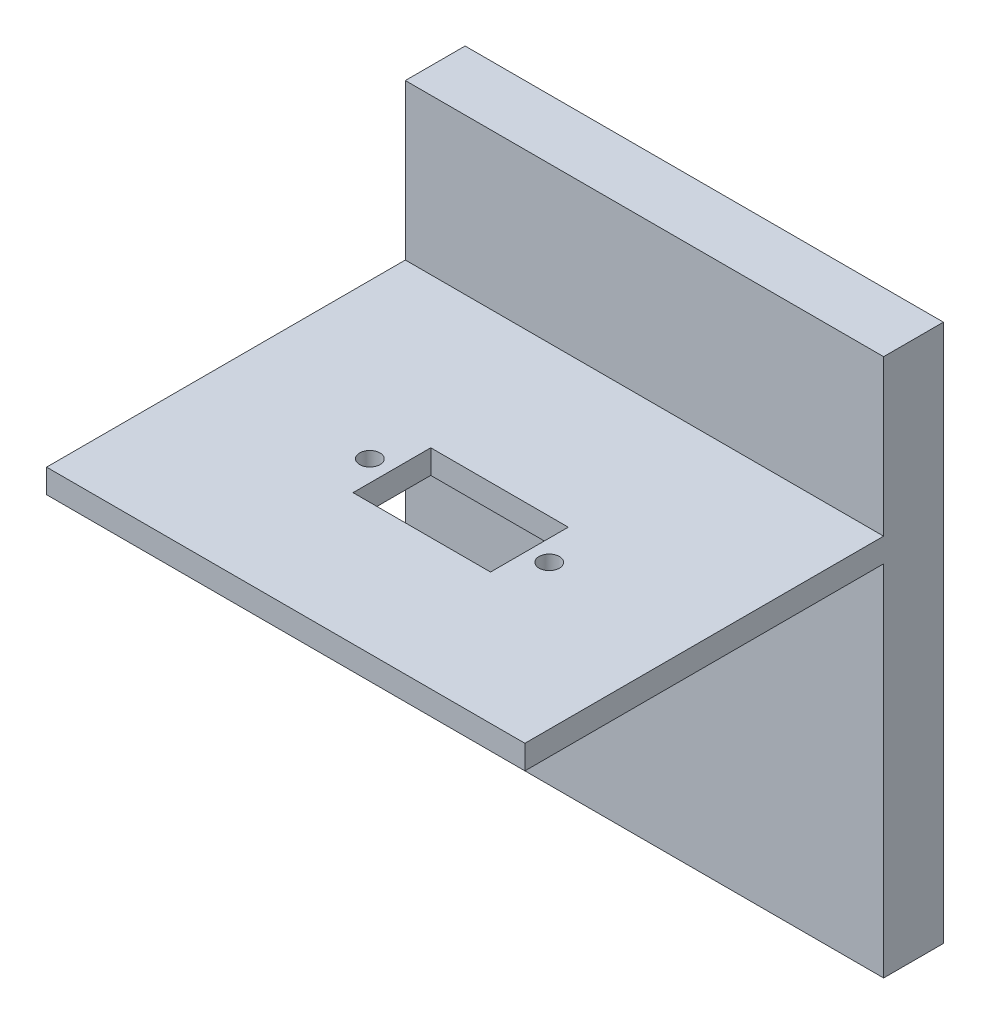
SolidWorks part; units mm, degrees
ref_plane "Front Plane" through (0, 0, 0) normal (0, 0, 1) x (1, 0, 0)
ref_plane "Top Plane" through (0, 0, 0) normal (0, 1, 0) x (1, 0, 0)
ref_plane "Right Plane" through (0, 0, 0) normal (1, 0, 0) x (0, 0, -1)
sketch "Sketch1" plane through (0, 0, 0) normal (0, 0, 1) x (1, 0, 0)
  line L0 (-48.2621, 36.3569) -> (-48.2621, -23.6431)
  line L14 (-48.2621, 36.3569) -> (-48.2621, 66.3569)
  line L15 (-48.2621, 66.3569) -> (31.7379, 66.3569)
  line L16 (31.7379, 36.3569) -> (31.7379, 66.3569)
  line L17 (-48.2621, -23.6431) -> (31.7379, -23.6431)
  line L18 (31.7379, -23.6431) -> (31.7379, 36.3569)
  point P5 (31.7379, -29.8051)
  dimension "D1" = 80
  dimension "D2" = 30
  dimension "D3" = 60
extrude "Base" add sketch "Sketch1" along normal blind 10
sketch "Sketch2" plane through (0, 0, 10) normal (0, 0, 1) x (1, 0, 0)
  line L0 (31.7379, -23.6431) -> (31.7379, 66.3569) construction
  line L1 (-48.2621, 36.3569) -> (31.7379, 36.3569)
  line L2 (-48.2621, 36.3569) -> (-48.2621, 40.3569)
  line L3 (-48.2621, 40.3569) -> (31.7379, 40.3569)
  line L4 (31.7379, 36.3569) -> (31.7379, 40.3569)
  dimension "D1" = 4
extrude "Shelf" add sketch "Sketch2" along normal blind 60
sketch "Sketch5" plane through (0, 40.3569, 0) normal (0, 1, 0) x (1, 0, 0)
  line L13 (-18.9379, -48.07) -> (4.0621, -48.07)
  line L14 (-18.9379, -48.07) -> (-18.9379, -35.07)
  line L15 (-18.9379, -35.07) -> (4.0621, -35.07)
  line L16 (4.0621, -48.07) -> (4.0621, -35.07)
  circle A0 centre (-22.4379, -41.7564) radius 1.7
  circle A1 centre (7.5621, -41.7564) radius 1.7
  dimension "D2" = 30
  dimension "D1" = 30
  dimension "D3" = 13
  dimension "D4" = 23
  dimension "D5" = 3.5
  dimension "D6" = 3.5
extrude "Cut-Extrude2" cut sketch "Sketch5" against normal blind 10
